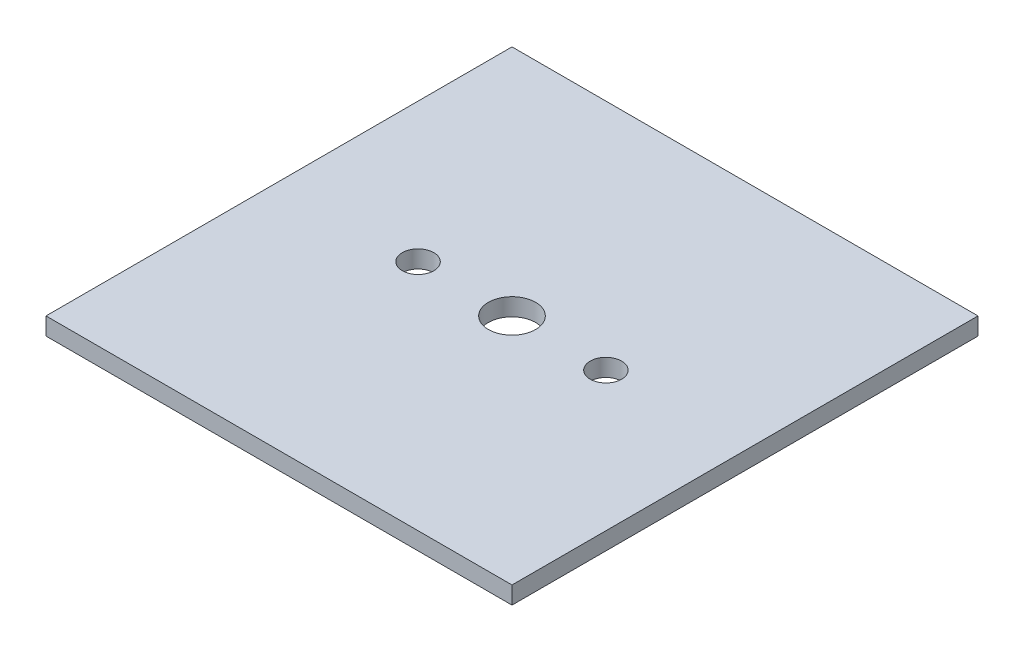
SolidWorks part; units mm, degrees
ref_plane "前视基准面" through (0, 0, 0) normal (0, 0, 1) x (1, 0, 0)
ref_plane "上视基准面" through (0, 0, 0) normal (0, 1, 0) x (1, 0, 0)
ref_plane "右视基准面" through (0, 0, 0) normal (1, 0, 0) x (0, 0, -1)
sketch "草图1" plane through (0, 0, 0) normal (0, 1, 0) x (1, 0, 0)
  line L1 (-40, -40) -> (40, -40)
  line L2 (-40, -40) -> (-40, 40)
  line L3 (-40, 40) -> (40, 40)
  line L4 (40, -40) -> (40, 40)
  line L5 (-40, -40) -> (40, 40) construction
  line L6 (-40, 40) -> (40, -40) construction
  point P0 (0, 0)
  dimension "D1" = 80
  dimension "D2" = 80
extrude "凸台-拉伸1" add sketch "草图1" along normal blind 3
sketch "草图2" plane through (0, 3, 0) normal (0, 1, 0) x (1, 0, 0)
  circle A0 centre (0, 0) radius 4.05
  dimension "D1" = 8.1
extrude "切除-拉伸1" cut sketch "草图2" against normal blind 3
sketch "草图3" plane through (0, 3, 0) normal (0, 1, 0) x (1, 0, 0)
  circle A0 centre (16.125, 0) radius 2.7
  circle A1 centre (-16.125, 0) radius 2.7
  dimension "D1" = 5.4
  dimension "D2" = 5.4
  dimension "D3" = 26.85
  dimension "D4" = 13.425
extrude "切除-拉伸2" cut sketch "草图3" against normal blind 3
